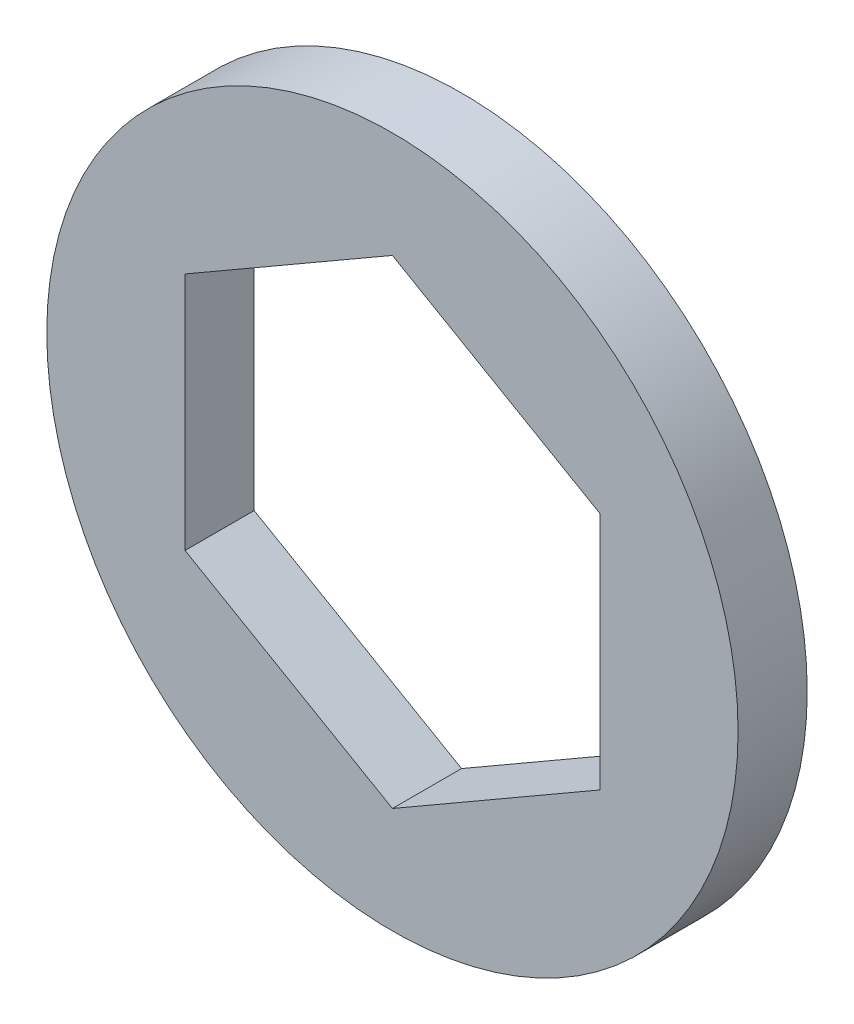
SolidWorks part; units mm, degrees
material "Delrin 2700 NC010, Low Viscosity Acetal Copolymer (SS)"
ref_plane "Front" through (0, 0, 0) normal (0, 0, 1) x (1, 0, 0)
ref_plane "Top" through (0, 0, 0) normal (0, 1, 0) x (1, 0, 0)
ref_plane "Right" through (0, 0, 0) normal (1, 0, 0) x (0, 0, -1)
sketch "Sketch1" plane through (0, 0, 0) normal (0, 0, 1) x (1, 0, 0)
  line L1 (-4.7625, 2.7496) -> (-4.7625, -2.7496)
  line L2 (-4.7625, -2.7496) -> (0, -5.4993)
  line L3 (0, -5.4993) -> (4.7625, -2.7496)
  line L4 (4.7625, -2.7496) -> (4.7625, 2.7496)
  line L5 (4.7625, 2.7496) -> (0, 5.4993)
  line L6 (0, 5.4993) -> (-4.7625, 2.7496)
  circle A0 centre (0, 0) radius 7.9375
  circle A1 centre (0, 0) radius 4.7625 construction
  dimension "D1" = 15.875
  dimension "D2" = 9.525
extrude "Spacer Boss" add sketch "Sketch1" along normal blind 1.5875
equation "\"HS\"=3 / 8'Hex Size"
equation "\"OD\"=.625'Outer Diameter"
equation "\"L\"=1 / 16'Length"
equation "\"D1@Sketch1\"=\"OD\""
equation "\"D2@Sketch1\"=\"HS\""
equation "\"D1@Spacer Boss\" = \"L\""
